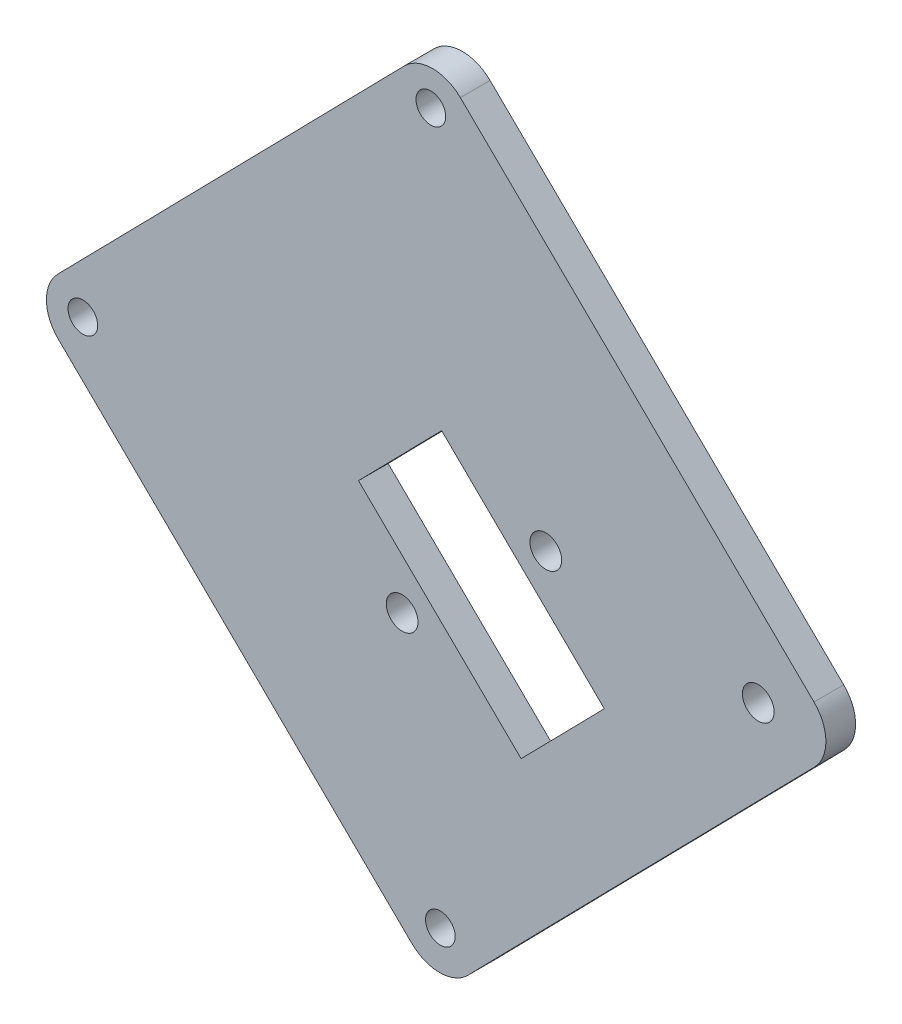
SolidWorks part; units mm, degrees
ref_plane "Plan de face" through (0, 0, 0) normal (0, 0, 1) x (1, 0, 0)
ref_plane "Plan de dessus" through (0, 0, 0) normal (0, 1, 0) x (1, 0, 0)
ref_plane "Plan de droite" through (0, 0, 0) normal (1, 0, 0) x (0, 0, -1)
sketch "Esquisse1" plane through (0, 0, 0) normal (0, 0, 1) x (1, 0, 0)
  line L0 (2.1604, 38.471) -> (37.8687, 3.4721)
  line L1 (-38.4382, -2.9506) -> (-2.7299, -37.9495)
  line L2 (-3.4962, 38.4142) -> (-38.495, 2.7059)
  line L3 (2.9266, -37.8927) -> (37.9255, -2.1844)
  line L4 (16.6974, -7.6994) -> (8.2977, -16.2694)
  line L5 (16.6974, -7.6994) -> (0.2716, 8.4)
  line L6 (8.2977, -16.2694) -> (-8.1281, -0.1699)
  line L7 (0.2716, 8.4) -> (-8.1281, -0.1699)
  arc A0 (-38.4382, -2.9506) -> (-38.495, 2.7059) centre (-35.6383, -0.094) cw
  arc A1 (-2.7299, -37.9495) -> (2.9266, -37.8927) centre (0.07, -35.0928) ccw
  arc A2 (37.8687, 3.4721) -> (37.9255, -2.1844) centre (35.0688, 0.6155) cw
  arc A3 (2.1604, 38.471) -> (-3.4962, 38.4142) centre (-0.6395, 35.6143) ccw
  circle A4 centre (-35.6383, -0.094) radius 1.6 construction
  circle A5 centre (-0.6395, 35.6143) radius 1.6 construction
  circle A6 centre (0.07, -35.0928) radius 1.6 construction
  circle A7 centre (10.7901, 3.1313) radius 1.6
  circle A8 centre (-3.7206, -9.5307) radius 1.6
  circle A9 centre (32.2405, 0.5871) radius 1.6
  dimension "D1" = 3.2
  dimension "D2" = 4
  dimension "D3" = 0.07
  dimension "D4" = 0.2716
  dimension "D5" = 2.1604
  dimension "D6" = 2.9266
  dimension "D7" = 8.2977
  dimension "D8" = 10.7901
  dimension "D9" = 16.6974
  dimension "D10" = 32.2405
  dimension "D11" = 0.5871
  dimension "D12" = 0.6155
  dimension "D13" = 8.4
  dimension "D14" = 3.1313
  dimension "D17" = 3.7206
  dimension "D26" = 9.5307
extrude "Boss.-Extru.1" add sketch "Esquisse1" along normal blind 3
sketch "Esquisse2" plane through (0, 0, 0) normal (0, 0, -1) x (-1, 0, 0)
  circle A0 centre (0.8209, 36.0721) radius 1.5
  circle A1 centre (35.9597, 0.221) radius 1.5
  circle A2 centre (-0.1414, -35.1628) radius 1.5
  dimension "D1" = 3
  dimension "D2" = 3
extrude "Enlèv. mat.-Extru.1" cut sketch "Esquisse2" against normal blind 10
